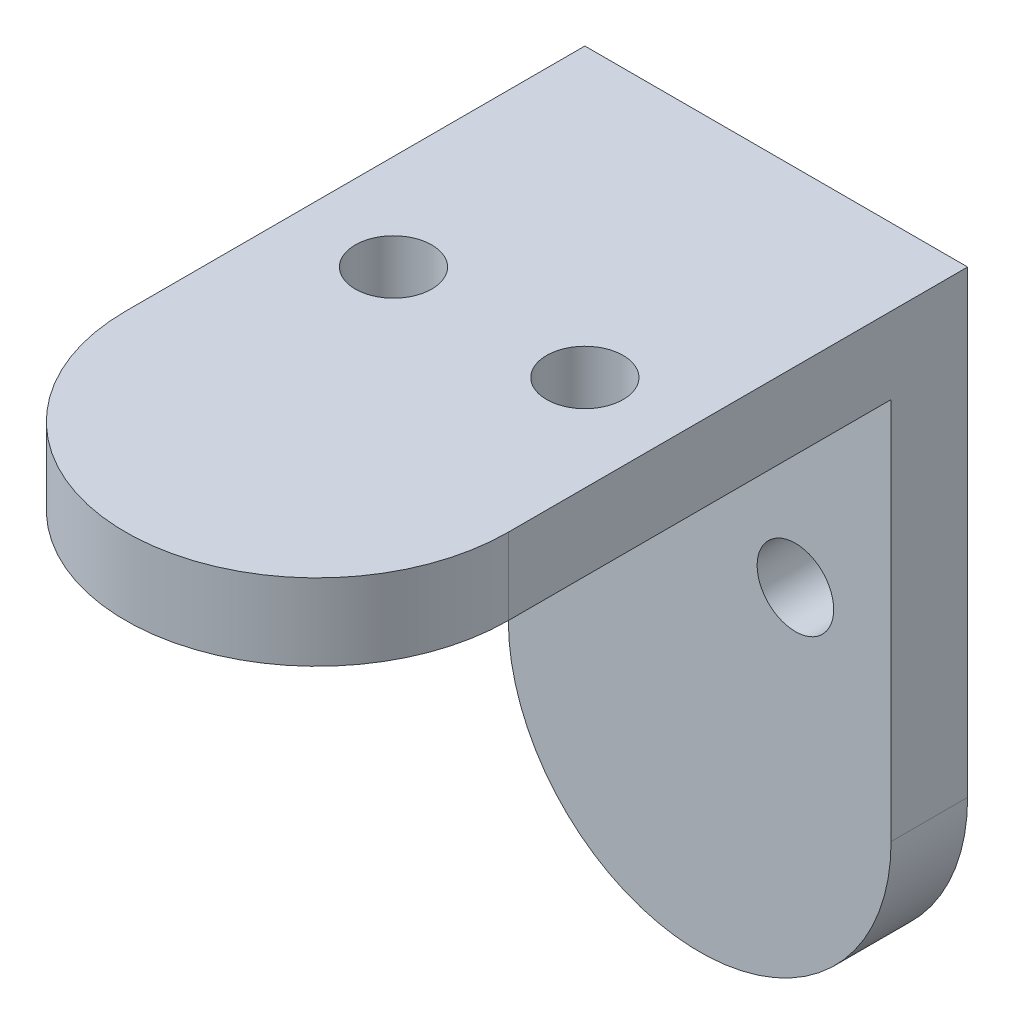
SolidWorks part; units mm, degrees
ref_plane "前视基准面" through (0, 0, 0) normal (0, 0, 1) x (1, 0, 0)
ref_plane "上视基准面" through (0, 0, 0) normal (0, 1, 0) x (1, 0, 0)
ref_plane "右视基准面" through (0, 0, 0) normal (1, 0, 0) x (0, 0, -1)
sketch "草图1" plane through (0, 0, 0) normal (0, 0, 1) x (1, 0, 0)
  line L1 (-20, 20) -> (20, 20)
  line L2 (-20, 20) -> (-20, -20)
  line L3 (-20, -20) -> (20, -20) construction
  line L4 (20, 20) -> (20, -20)
  line L5 (0, -20) -> (0, 20) construction
  line L6 (-20, 0) -> (20, 0) construction
  arc A0 (-20, -20) -> (20, -20) centre (0, -20) ccw
  point P0 (0, 0)
  dimension "D1" = 40
extrude "凸台-拉伸1" add sketch "草图1" along normal blind 8
sketch "草图2" plane through (0, 20, 0) normal (0, 1, 0) x (1, 0, 0)
  line L5 (-20, 0) -> (20, 0)
  line L6 (-20, 0) -> (-20, -48)
  line L7 (-20, -48) -> (20, -48) construction
  line L8 (20, 0) -> (20, -48)
  arc A0 (-20, -48) -> (20, -48) centre (0, -48) ccw
  dimension "D1" = 40
  dimension "D2" = 48
extrude "凸台-拉伸2" add sketch "草图2" along normal blind 8
sketch "草图3" plane through (0, 0, 0) normal (0, 0, -1) x (-1, 0, 0)
  line L1 (-20, -20) -> (-20, 28) construction
  line L3 (-20, 28) -> (20, 28) construction
  line L4 (20, 28) -> (20, -20) construction
  circle A0 centre (-10, -2) radius 4
  circle A1 centre (10, -2) radius 4
  dimension "D1" = 10
  dimension "D5" = 8
  dimension "D6" = 8
  dimension "D2" = 20
  dimension "D3" = 10
  dimension "D4" = 30
sketch "草图4" plane through (0, 28, 0) normal (0, 1, 0) x (1, 0, 0)
  line L0 (20, 0) -> (-20, 0) construction
  line L1 (-20, 0) -> (-20, -48) construction
  circle A0 centre (-10, -30) radius 4
  circle A1 centre (10, -30) radius 4
  dimension "D1" = 8
  dimension "D2" = 8
  dimension "D3" = 30
  dimension "D4" = 10
  dimension "D5" = 20
  dimension "D6" = 30
extrude "切除-拉伸1" cut sketch "草图3" against normal up to next
extrude "切除-拉伸2" cut sketch "草图4" against normal up to next
